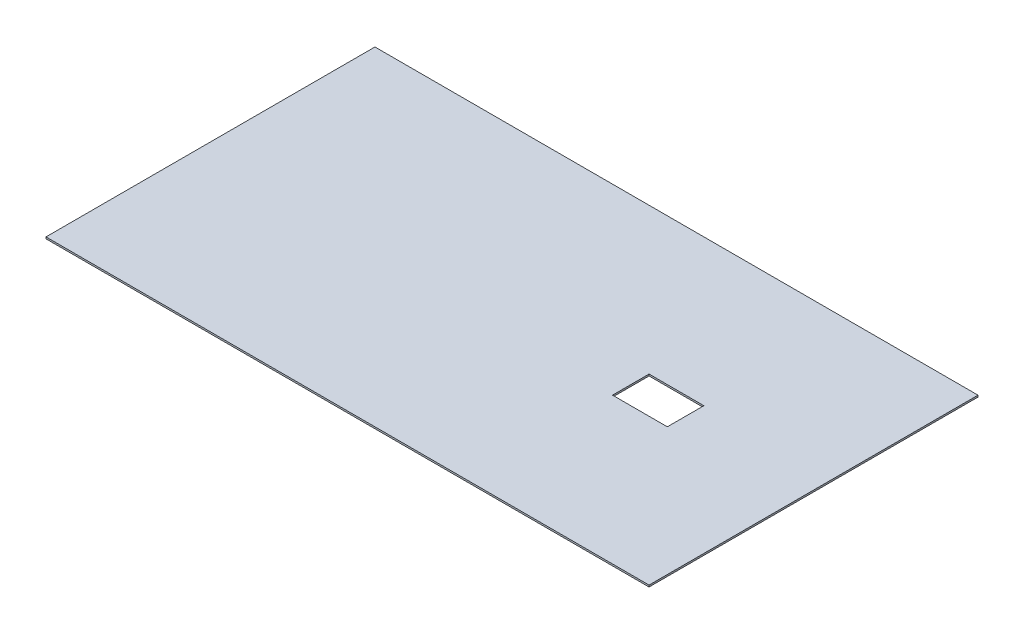
SolidWorks part; units mm, degrees
ref_plane "Front Plane" through (0, 0, 0) normal (0, 0, 1) x (1, 0, 0)
ref_plane "Top Plane" through (0, 0, 0) normal (0, 1, 0) x (1, 0, 0)
ref_plane "Right Plane" through (0, 0, 0) normal (1, 0, 0) x (0, 0, -1)
sketch "Sketch1" plane through (0, 0, 0) normal (0, 1, 0) x (1, 0, 0)
  line L1 (0, 0) -> (838.2, 0)
  line L2 (0, 0) -> (0, 457.2)
  line L3 (0, 457.2) -> (838.2, 457.2)
  line L4 (838.2, 0) -> (838.2, 457.2)
  dimension "D1" = 838.2
  dimension "D2" = 457.2
extrude "Boss-Extrude1" add sketch "Sketch1" along normal blind 2.3813
sketch "Sketch3" plane through (0, 2.3813, 0) normal (0, 1, 0) x (1, 0, 0)
  line L0 (425.45, 457.2) -> (857.25, 457.2) construction
  line L1 (660.4, 254) -> (584.2, 254)
  line L2 (660.4, 254) -> (660.4, 203.2)
  line L3 (660.4, 203.2) -> (584.2, 203.2)
  line L4 (584.2, 254) -> (584.2, 203.2)
  line L5 (838.2, -254) -> (838.2, 457.2) construction
  dimension "D1" = 203.2
  dimension "D2" = 177.8
  dimension "D3" = 76.2
  dimension "D4" = 50.8
extrude "Cut-Extrude1" cut sketch "Sketch3" against normal through all
sketch "Sketch4" plane through (0, 2.3813, 0) normal (0, 1, 0) x (1, 0, 0)
  line L0 (0, 457.2) -> (0, 0) construction
  line L1 (0, 203.2) -> (88.9, 203.2)
  line L2 (0, 203.2) -> (0, 254)
  line L3 (0, 254) -> (88.9, 254)
  line L4 (88.9, 203.2) -> (88.9, 254)
  line L5 (838.2, -254) -> (838.2, 457.2) construction
  line L6 (838.2, 203.2) -> (749.3, 203.2)
  line L7 (838.2, 203.2) -> (838.2, 254)
  line L8 (838.2, 254) -> (749.3, 254)
  line L9 (749.3, 203.2) -> (749.3, 254)
  line L10 (425.45, 457.2) -> (857.25, 457.2) construction
  line L11 (838.2, 457.2) -> (0, 457.2) construction
  dimension "D1" = 88.9
  dimension "D2" = 50.8
  dimension "D3" = 203.2
  dimension "D4" = 203.2
